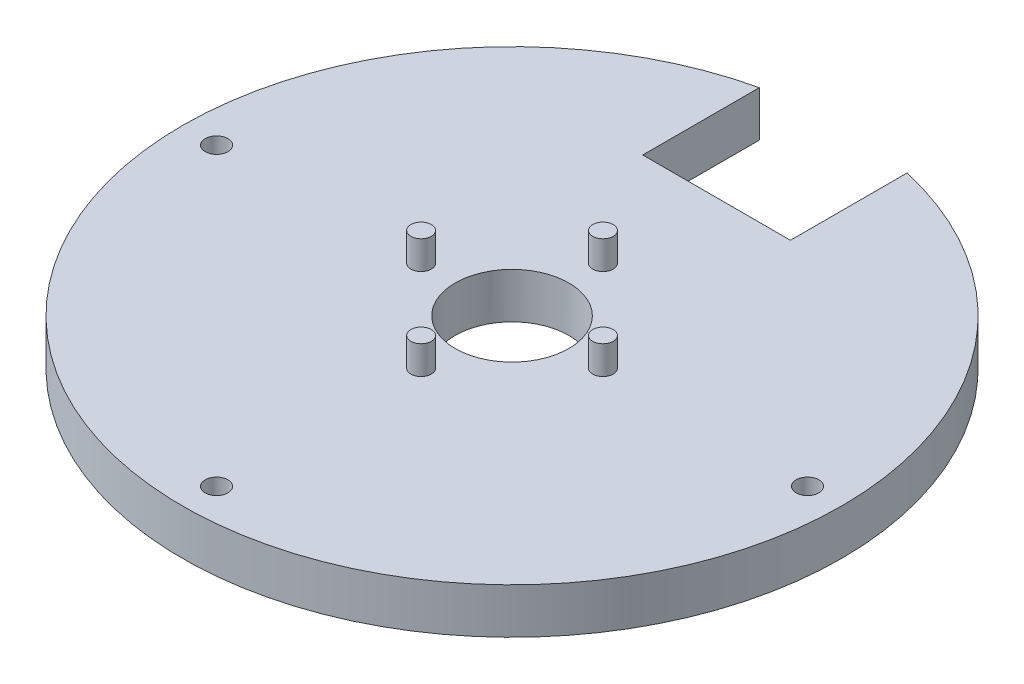
SolidWorks part; units mm, degrees
ref_plane "Front Plane" through (0, 0, 0) normal (0, 0, 1) x (1, 0, 0)
ref_plane "Top Plane" through (0, 0, 0) normal (0, 1, 0) x (1, 0, 0)
ref_plane "Right Plane" through (0, 0, 0) normal (1, 0, 0) x (0, 0, -1)
sketch "Sketch1" plane through (0, 0, 0) normal (0, 1, 0) x (1, 0, 0)
  circle A0 centre (0, 0) radius 29
extrude "Boss-Extrude1" add sketch "Sketch1" along normal blind 5 contours A0
sketch "Sketch3" plane through (0, 5, 0) normal (0, 1, 0) x (1, 0, 0)
  line L1 (-6.5, 29) -> (6.5, 29)
  line L2 (-6.5, 29) -> (-6.5, 18)
  line L3 (6.5, 29) -> (6.5, 18)
  line L4 (-6.5, 18) -> (6.5, 18)
  point P8 (0, 29)
extrude "Cut-Extrude1" cut sketch "Sketch3" against normal blind 10
sketch "Sketch4" plane through (0, 5, 0) normal (0, 1, 0) x (1, 0, 0)
  circle A0 centre (8, 0) radius 0.9
  circle A1 centre (-8, 0) radius 0.9
  circle A2 centre (0, 8) radius 0.9
  circle A3 centre (0, -8) radius 0.9
  point P1 (0, 0)
  point P10 (0, 0)
  point P11 (0, 0)
extrude "Boss-Extrude2" add sketch "Sketch4" along normal blind 2.5
sketch "Sketch5" plane through (0, 5, 0) normal (0, 1, 0) x (1, 0, 0)
  circle A2 centre (-20, 0) radius 1
  circle A3 centre (20, 0) radius 1
  circle A4 centre (0, -20) radius 1
sketch "Sketch6" plane through (0, 0, 0) normal (0, -1, 0) x (-1, 0, 0)
  circle A1 centre (0, 0) radius 29
sketch "Sketch7" plane through (0, 5, 0) normal (0, 1, 0) x (1, 0, 0)
  circle A0 centre (0, 0) radius 5
extrude "Cut-Extrude4" cut sketch "Sketch7" against normal blind 5
ref_plane "Plane1" through (6.5, 5, -28.2622) normal (-0.9746, 0, -0.2241) x (-0.2241, 0, 0.9746)
sketch "Sketch10" plane through (0, 5, 0) normal (0, 1, 0) x (1, 0, 0)
  circle A0 centre (0, 0) radius 29
sketch "Sketch11" plane through (0, 5, 0) normal (0, 1, 0) x (1, 0, 0)
  circle A0 centre (-26, 0) radius 1
  circle A1 centre (0, -26) radius 1
  circle A2 centre (26, 0) radius 1
  point P0 (0, 0)
extrude "Cut-Extrude6" cut sketch "Sketch11" against normal blind 5
sketch "Sketch12" plane through (0, 0, 0) normal (0, -1, 0) x (-1, 0, 0)
  circle A0 centre (0, 0) radius 29
extrude "Cut-Extrude7" cut sketch "Sketch12" against normal blind 1
